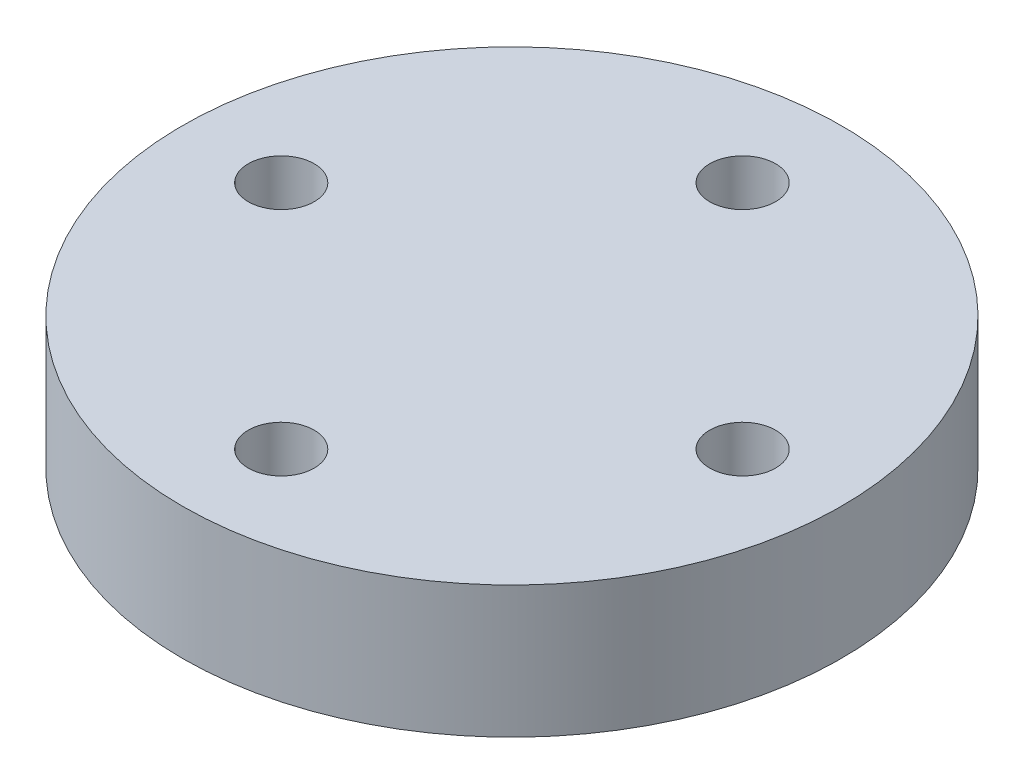
SolidWorks part; units mm, degrees
ref_plane "Спереди" through (0, 0, 0) normal (0, 0, 1) x (1, 0, 0)
ref_plane "Сверху" through (0, 0, 0) normal (0, 1, 0) x (1, 0, 0)
ref_plane "Справа" through (0, 0, 0) normal (1, 0, 0) x (0, 0, -1)
sketch "Эскиз1" plane through (0, 0, 0) normal (0, 1, 0) x (1, 0, 0)
  circle A0 centre (0, 0) radius 10
  circle A1 centre (0, 0) radius 7 construction
  circle A2 centre (0, 0) radius 8 construction
  circle A3 centre (0, 7) radius 1
  circle A4 centre (7, 0) radius 1
  circle A5 centre (0, -7) radius 1
  circle A6 centre (-7, 0) radius 1
  dimension "D1" = 14
  dimension "D2" = 16
  dimension "D3" = 20
extrude "Бобышка-Вытянуть1" add sketch "Эскиз1" along normal blind 4
